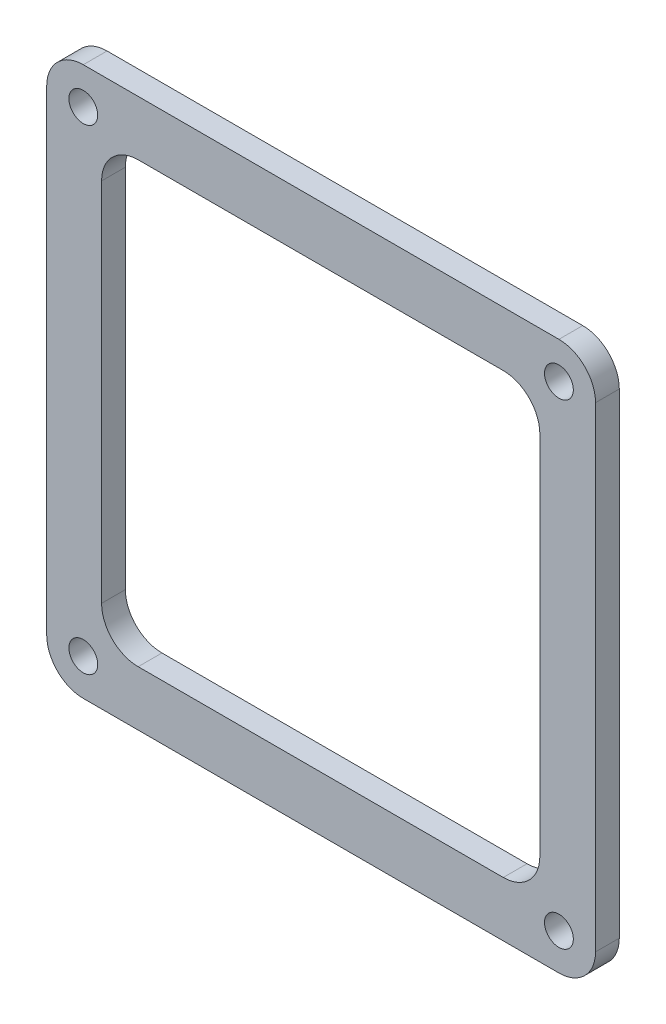
SolidWorks part; units mm, degrees
ref_plane "前视基准面" through (0, 0, 0) normal (0, 0, 1) x (1, 0, 0)
ref_plane "上视基准面" through (0, 0, 0) normal (0, 1, 0) x (1, 0, 0)
ref_plane "右视基准面" through (0, 0, 0) normal (1, 0, 0) x (0, 0, -1)
sketch "Model" plane through (0, 0, 0) normal (0, 0, 1) x (1, 0, 0)
  line L0 (2267.0871, 1815.3589) -> (2267.0871, 1763.3589)
  line L1 (2271.0871, 1759.3589) -> (2323.0871, 1759.3589)
  line L2 (2327.0871, 1763.3589) -> (2327.0871, 1815.3589)
  line L3 (2295.4835, 1813.3576) -> (2317.0005, 1813.3576)
  line L4 (2321.0005, 1809.3576) -> (2321.0005, 1769.3624)
  line L5 (2317.0005, 1765.3624) -> (2277.0871, 1765.3624)
  line L6 (2273.0871, 1769.3624) -> (2273.0871, 1809.3576)
  line L7 (2277.0871, 1813.3576) -> (2295.4835, 1813.3576)
  line L8 (2271.0871, 1819.3589) -> (2323.0871, 1819.3589)
  arc A0 (2327.0871, 1815.3589) -> (2323.0871, 1819.3589) centre (2323.0871, 1815.3589) ccw
  arc A1 (2271.0871, 1819.3589) -> (2267.0871, 1815.3589) centre (2271.0871, 1815.3589) ccw
  arc A2 (2267.0871, 1763.3589) -> (2271.0871, 1759.3589) centre (2271.0871, 1763.3589) ccw
  arc A3 (2323.0871, 1759.3589) -> (2327.0871, 1763.3589) centre (2323.0871, 1763.3589) ccw
  circle A4 centre (2271.0871, 1763.3589) radius 1.575
  circle A5 centre (2323.0871, 1763.3589) radius 1.575
  circle A6 centre (2271.0871, 1815.3589) radius 1.575
  circle A7 centre (2323.0871, 1815.3589) radius 1.575
  arc A8 (2321.0005, 1809.3576) -> (2317.0005, 1813.3576) centre (2317.0005, 1809.3576) ccw
  arc A9 (2317.0005, 1765.3624) -> (2321.0005, 1769.3624) centre (2317.0005, 1769.3624) ccw
  arc A10 (2273.0871, 1769.3624) -> (2277.0871, 1765.3624) centre (2277.0871, 1769.3624) ccw
  arc A11 (2277.0871, 1813.3576) -> (2273.0871, 1809.3576) centre (2277.0871, 1809.3576) ccw
extrude "凸台-拉伸1" add sketch "Model" along normal blind 2.6
